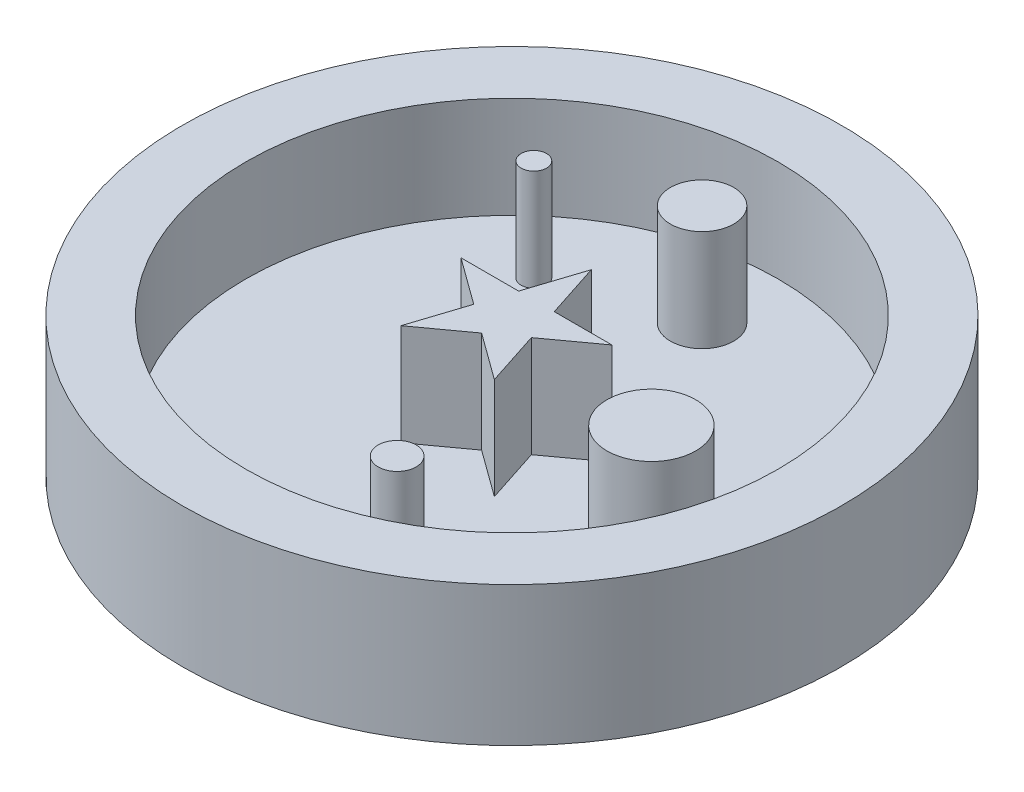
SolidWorks part; units mm, degrees
ref_plane "Front Plane" through (0, 0, 0) normal (0, 0, 1) x (1, 0, 0)
ref_plane "Top Plane" through (0, 0, 0) normal (0, 1, 0) x (1, 0, 0)
ref_plane "Right Plane" through (0, 0, 0) normal (1, 0, 0) x (0, 0, -1)
sketch "Sketch1" plane through (0, 0, 0) normal (0, 1, 0) x (1, 0, 0)
  circle A0 centre (0, 0) radius 26
  dimension "D1" = 52
extrude "Boss-Extrude1" add sketch "Sketch1" along normal blind 11
sketch "Sketch2" plane through (0, 11, 0) normal (0, 1, 0) x (1, 0, 0)
  circle A0 centre (0, 0) radius 21
  circle A2 centre (0, 0) radius 26 construction
  dimension "D1" = 42
  dimension "D2" = 5
extrude "Cut-Extrude1" cut sketch "Sketch2" against normal blind 8
sketch "Sketch3" plane through (0, 3, 0) normal (0, 1, 0) x (1, 0, 0)
  line L10 (0, 6.261) -> (-1.4057, 1.9348)
  line L11 (0, 6.261) -> (-5.9546, 1.9348) construction
  line L27 (-5.9546, 1.9348) -> (-3.6801, -5.0652) construction
  line L28 (-3.6801, -5.0652) -> (3.6801, -5.0652) construction
  line L29 (3.6801, -5.0652) -> (5.9546, 1.9348) construction
  line L30 (5.9546, 1.9348) -> (0, 6.261) construction
  line L31 (-3.6801, -5.0652) -> (0, -2.3915)
  line L32 (5.9546, 1.9348) -> (1.4057, 1.9348)
  line L33 (-5.9546, 1.9348) -> (-2.2744, -0.739)
  line L34 (3.6801, -5.0652) -> (2.2744, -0.739)
  line L35 (-1.4057, 1.9348) -> (-5.9546, 1.9348)
  line L36 (1.4057, 1.9348) -> (0, 6.261)
  line L37 (-2.2744, -0.739) -> (-3.6801, -5.0652)
  line L38 (0, -2.3915) -> (3.6801, -5.0652)
  line L39 (2.2744, -0.739) -> (5.9546, 1.9348)
  circle A0 centre (0, 0) radius 5.0652 construction
  dimension "D1" = 7
extrude "Boss-Extrude2" add sketch "Sketch3" along normal blind 8
sketch "Sketch5" plane through (0, 3, 0) normal (0, 1, 0) x (1, 0, 0)
  circle A0 centre (-9.7067, 11.4359) radius 1
  point P2 (-9.2415, 11.815)
  dimension "D1" = 2
  dimension "D2" = 15
  dimension "D3" = 11
extrude "Boss-Extrude3" add sketch "Sketch5" along normal blind 8
sketch "Sketch6" plane through (0, 3, 0) normal (0, 1, 0) x (1, 0, 0)
  circle A0 centre (0, 15) radius 2.5
  point P2 (-0.5418, 14.2673)
  point P5 (1.3791, 14.7612)
  point P8 (0, 15)
  point P9 (0, 0)
  dimension "D1" = 5
  dimension "D2" = 15
  dimension "D3" = 8.739
extrude "Boss-Extrude4" add sketch "Sketch6" along normal blind 8
sketch "Sketch7" plane through (0, 3, 0) normal (0, 1, 0) x (1, 0, 0)
  circle A0 centre (13, -2) radius 3.5
  dimension "D1" = 7
  dimension "D3" = 15.4027
  dimension "D2" = 13
extrude "Boss-Extrude5" add sketch "Sketch7" along normal blind 8
sketch "Sketch11" plane through (0, 3, 0) normal (0, 1, 0) x (1, 0, 0)
  circle A0 centre (5.0645, -14.1192) radius 1.5
  point P2 (9.5, -11.6029)
  dimension "D1" = 3
  dimension "D2" = 15
  dimension "D3" = 21
extrude "Boss-Extrude6" add sketch "Sketch11" along normal blind 8
